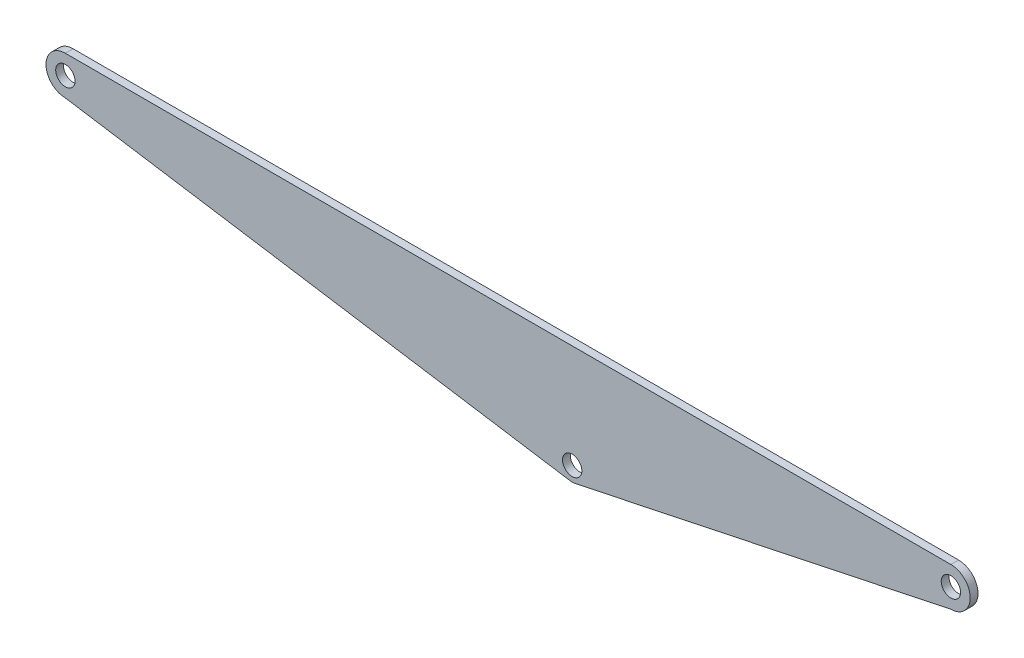
SolidWorks part; units mm, degrees
ref_plane "Front Plane" through (0, 0, 0) normal (0, 0, 1) x (1, 0, 0)
ref_plane "Top Plane" through (0, 0, 0) normal (0, 1, 0) x (1, 0, 0)
ref_plane "Right Plane" through (0, 0, 0) normal (1, 0, 0) x (0, 0, -1)
sketch "Sketch1" plane through (0, 0, 0) normal (0, 0, 1) x (1, 0, 0)
  line L0 (0, 0) -> (-580.7, 0) construction
  line L1 (0, 0) -> (-248.347, -55.1645) construction
  line L2 (-580.7, 0) -> (-580.7, 12.7) construction
  line L3 (-580.7, 0) -> (-580.7, -12.7) construction
  line L4 (-580.7, 0) -> (-593.4, 0) construction
  line L5 (0, 0) -> (12.7, 0) construction
  line L6 (0, 0) -> (0, 12.7) construction
  line L7 (0, 0) -> (0, -12.7) construction
  line L8 (-580.7, 12.7) -> (0, 12.7)
  line L9 (0, -12.7) -> (-246.3878, -64.4859)
  line L10 (-580.7, -12.7) -> (-249.8223, -64.5746)
  circle A0 centre (0, 0) radius 6.35
  circle A1 centre (-580.7, 0) radius 6.35
  circle A2 centre (-248.347, -55.1645) radius 6.35
  arc A3 (-580.7, 12.7) -> (-580.7, -12.7) centre (-580.7, 0) ccw
  arc A4 (0, 12.7) -> (0, -12.7) centre (0, 0) cw
  arc A5 (-249.8223, -64.5746) -> (-246.3878, -64.4859) centre (-248.347, -55.1645) ccw
  dimension "D1" = 12.7
  dimension "D3" = 12.7
  dimension "D4" = 12.7
  dimension "D13" = 19.05
  dimension "D2" = 580.7
  dimension "D5" = 254.4
  dimension "D6" = 12.524
  dimension "D7" = 12.7
  dimension "D8" = 12.7
  dimension "D9" = 12.7
  dimension "D10" = 12.7
  dimension "D11" = 12.7
extrude "Boss-Extrude1" add sketch "Sketch1" against normal blind 5.08
ref_point "Point1"
ref_point "Point2"
